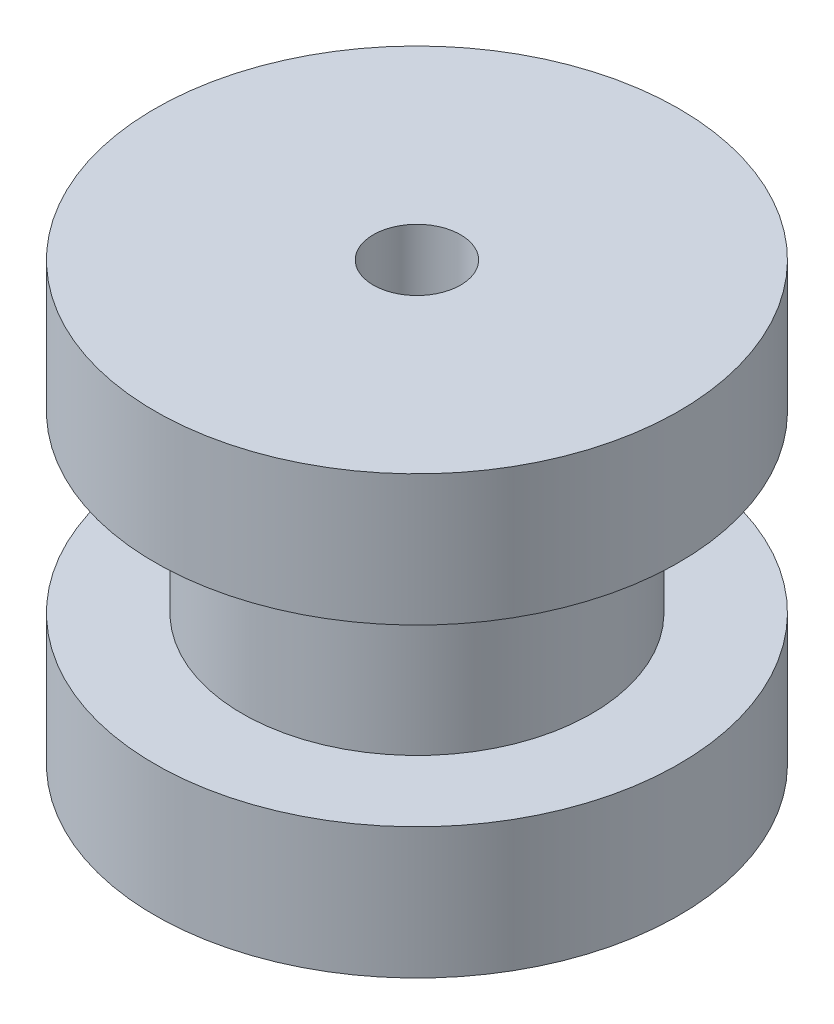
SolidWorks part; units mm, degrees
ref_plane "Alzado" through (0, 0, 0) normal (0, 0, 1) x (1, 0, 0)
ref_plane "Planta" through (0, 0, 0) normal (0, 1, 0) x (1, 0, 0)
ref_plane "Vista lateral" through (0, 0, 0) normal (1, 0, 0) x (0, 0, -1)
sketch "Croquis1" plane through (0, 0, 0) normal (0, 0, 1) x (1, 0, 0)
  line L0 (0.9, 20) -> (0.9, 5)
  line L1 (6, 5) -> (6, 2)
  line L2 (6, -5) -> (0.9, -5)
  line L3 (6, 5) -> (0.9, 5)
  line L4 (0, 0) -> (0, 50000) construction
  line L5 (0.9, 20) -> (0, 20)
  line L6 (0, 20) -> (0, -20)
  line L7 (0, -20) -> (0.9, -20)
  line L8 (0.9, -5) -> (0.9, -20)
  line L9 (6, 2) -> (4, 2)
  line L10 (4, 2) -> (4, -2)
  line L11 (4, -2) -> (6, -2)
  line L12 (4, 0) -> (6, 0) construction
  line L13 (6, 2) -> (6, 0) construction
  line L14 (6, -2) -> (6, -5)
  line L15 (6, 0) -> (6, -2) construction
  point P3 (0.9, 0)
  point P6 (6, 0)
  point P13 (0, 0)
  dimension "D1" = 40
  dimension "D2" = 1.8
  dimension "D3" = 10
  dimension "D4" = 12
  dimension "D5" = 2
  dimension "D6" = 4
revolve "Revolución1" add sketch "Croquis1" angle 360 about L4
sketch "Croquis2" plane through (0, 20, 0) normal (0, 1, 0) x (1, 0, 0)
  circle A0 centre (0, 0) radius 0.5
  dimension "D1" = 1
extrude "Cortar-Extruir1" cut sketch "Croquis2" against normal through all both and the other way through all
sketch "Croquis3" plane through (0, 5, 0) normal (0, 1, 0) x (1, 0, 0)
  circle A0 centre (0, 0) radius 1
  dimension "D1" = 2
extrude "Cortar-Extruir2" cut sketch "Croquis3" against normal through all both and the other way through all
